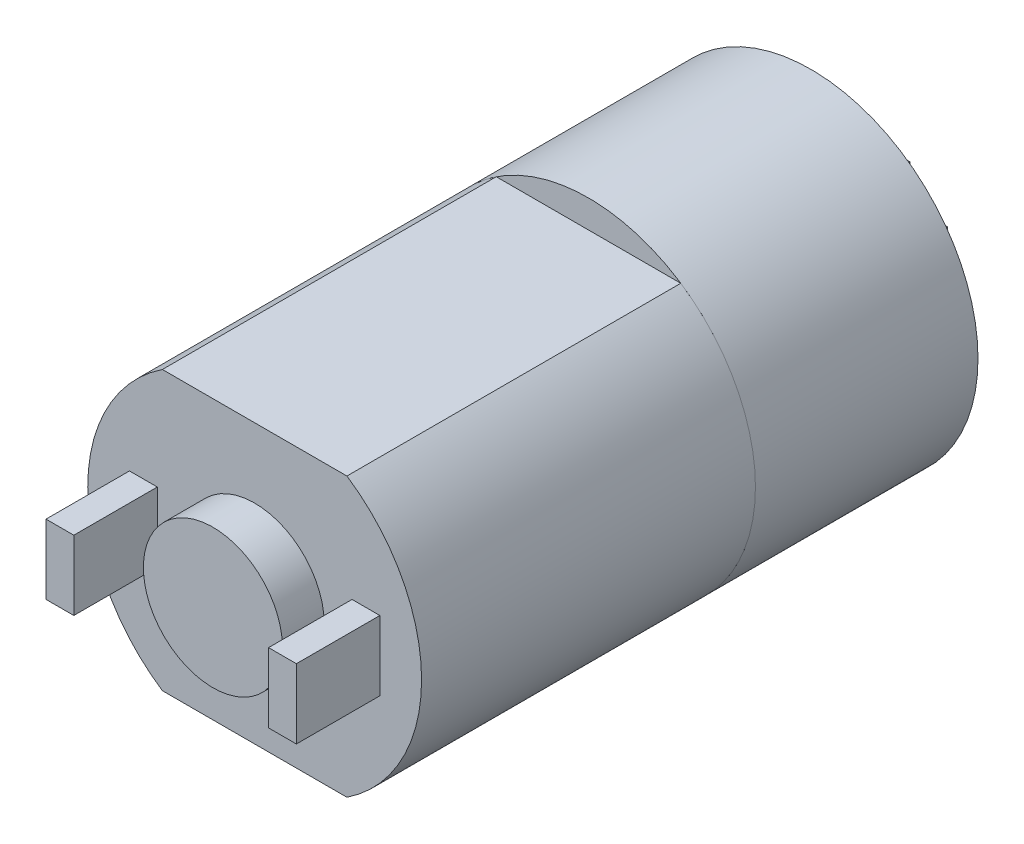
SolidWorks part; units mm, degrees
ref_plane "Alzado" through (0, 0, 0) normal (0, 0, 1) x (1, 0, 0)
ref_plane "Planta" through (0, 0, 0) normal (0, 1, 0) x (1, 0, 0)
ref_plane "Vista lateral" through (0, 0, 0) normal (1, 0, 0) x (0, 0, -1)
sketch "Croquis1" plane through (0, 0, 0) normal (0, 0, 1) x (1, 0, 0)
  circle A0 centre (0, 0) radius 6
  dimension "D1" = 12
extrude "Saliente-Extruir1" add sketch "Croquis1" along normal blind 8
sketch "Croquis2" plane through (0, 0, 8) normal (0, 0, 1) x (1, 0, 0)
  line L0 (5.3894, 5) -> (-49994.6106, 5) construction
  line L1 (5.3894, -5) -> (-49994.6106, -5) construction
  line L2 (3.3166, 5) -> (-3.3166, 5)
  line L3 (3.3166, -5) -> (-3.3166, -5)
  line L4 (-0.067, 0) -> (-50000.067, 0) construction
  arc A2 (-3.3166, -5) -> (-3.3166, 5) centre (0, 0) cw
  arc A4 (3.3166, 5) -> (3.3166, -5) centre (0, 0) cw
  circle A5 centre (0, 0) radius 6 construction
  dimension "D1" = 10
extrude "Saliente-Extruir2" add sketch "Croquis2" along normal blind 12 separate body
sketch "Croquis3" plane through (0, 0, 0) normal (0, 0, -1) x (-1, 0, 0)
  line L0 (-2.2, 0.85) -> (-0.85, 0.85)
  line L1 (-0.85, 2.2) -> (0.85, 2.2) construction
  line L2 (-0.85, 2.2) -> (-0.85, -2.2) construction
  line L3 (-0.85, -2.2) -> (0.85, -2.2) construction
  line L4 (0.85, 2.2) -> (0.85, -2.2) construction
  line L5 (-0.85, 2.2) -> (0.85, -2.2) construction
  line L6 (-0.85, -2.2) -> (0.85, 2.2) construction
  line L7 (-2.2, 0.85) -> (2.2, 0.85) construction
  line L8 (-2.2, 0.85) -> (-2.2, -0.85) construction
  line L9 (-2.2, -0.85) -> (2.2, -0.85) construction
  line L10 (2.2, 0.85) -> (2.2, -0.85) construction
  line L11 (-2.2, 0.85) -> (2.2, -0.85) construction
  line L12 (-2.2, -0.85) -> (2.2, 0.85) construction
  line L13 (-0.85, 0.85) -> (-0.85, 2.2)
  line L14 (-0.85, 2.2) -> (0.85, 2.2)
  line L15 (0.85, 2.2) -> (0.85, 0.85)
  line L16 (0.85, 0.85) -> (2.2, 0.85)
  line L17 (2.2, 0.85) -> (2.2, -0.85)
  line L18 (2.2, -0.85) -> (0.85, -0.85)
  line L19 (0.85, -0.85) -> (0.85, -2.2)
  line L20 (0.85, -2.2) -> (-0.85, -2.2)
  line L21 (-0.85, -2.2) -> (-0.85, -0.85)
  line L22 (-0.85, -0.85) -> (-2.2, -0.85)
  line L23 (-2.2, -0.85) -> (-2.2, 0.85)
  point P0 (0, 0)
  point P6 (0, 0)
  dimension "D1" = 1.7
  dimension "D2" = 4.4
extrude "Saliente-Extruir3" add sketch "Croquis3" along normal blind 2.7
sketch "Croquis4" plane through (0, 0, -2.7) normal (0, 0, -1) x (-1, 0, 0)
  circle A0 centre (0, 0) radius 0.7523
  dimension "D1" = 1.5046
extrude "Saliente-Extruir4" add sketch "Croquis4" along normal blind 0.8
sketch "Croquis5" plane through (0, 0, 20) normal (0, 0, 1) x (1, 0, 0)
  circle A0 centre (0, 0) radius 2.5
  dimension "D1" = 5
extrude "Saliente-Extruir5" add sketch "Croquis5" along normal blind 1.5
sketch "Croquis6" plane through (0, 0, 20) normal (0, 0, 1) x (1, 0, 0)
  line L0 (0, 0) -> (-50000, 0) construction
  line L1 (0, 0) -> (0, 50000) construction
  line L2 (-4.5, 1.25) -> (-3.5, 1.25)
  line L3 (-4.5, 1.25) -> (-4.5, -1.25)
  line L4 (-4.5, -1.25) -> (-3.5, -1.25)
  line L5 (-3.5, 1.25) -> (-3.5, -1.25)
  line L6 (-4.5, 1.25) -> (-3.5, -1.25) construction
  line L7 (-4.5, -1.25) -> (-3.5, 1.25) construction
  line L8 (4.5, -1.25) -> (3.5, 1.25) construction
  line L9 (4.5, 1.25) -> (3.5, -1.25) construction
  line L10 (3.5, 1.25) -> (3.5, -1.25)
  line L11 (4.5, -1.25) -> (3.5, -1.25)
  line L12 (4.5, 1.25) -> (4.5, -1.25)
  line L13 (4.5, 1.25) -> (3.5, 1.25)
  point P3 (-4, 0)
  point P14 (4, 0)
  dimension "D1" = 1
  dimension "D2" = 2.5
  dimension "D3" = 8
extrude "Saliente-Extruir6" add sketch "Croquis6" along normal blind 3 separate body
